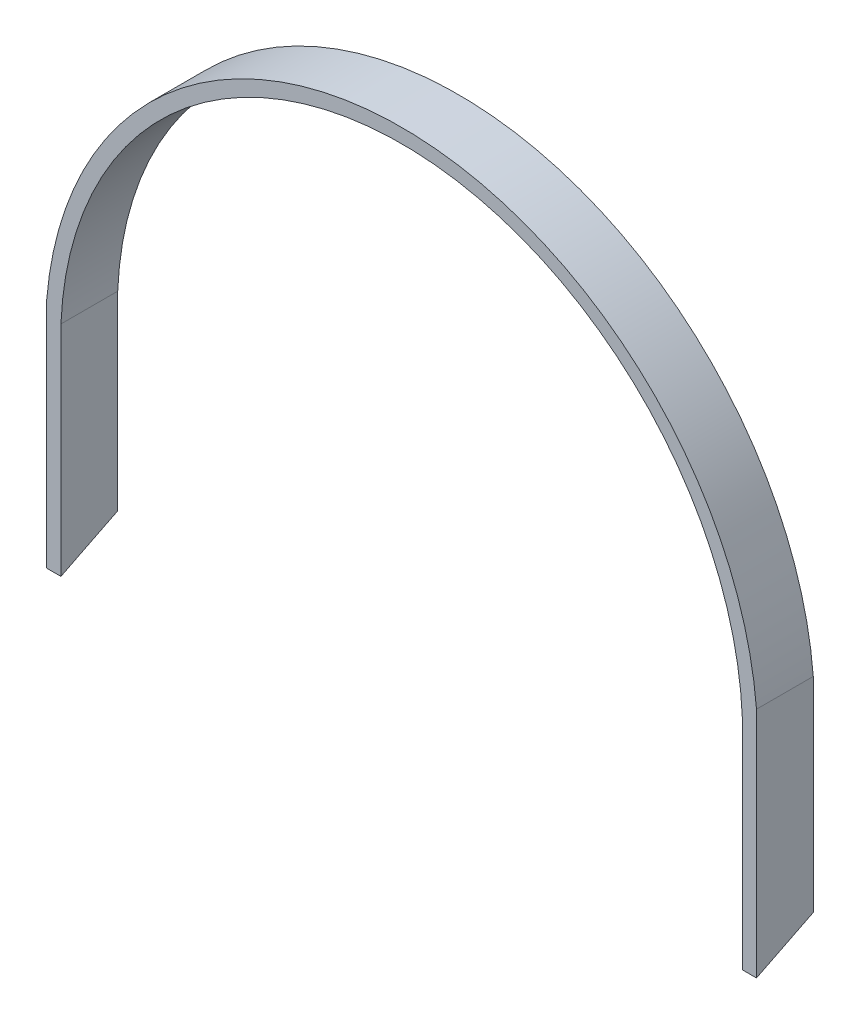
SolidWorks part; units mm, degrees
material "ABS"
ref_plane "Plan de face" through (0, 0, 0) normal (0, 0, 1) x (1, 0, 0)
ref_plane "Plan de dessus" through (0, 0, 0) normal (0, 1, 0) x (1, 0, 0)
ref_plane "Plan de droite" through (0, 0, 0) normal (1, 0, 0) x (0, 0, -1)
sketch "Esquisse1" plane through (0, 0, 0) normal (0, 0, 1) x (1, 0, 0)
  line L2 (0, 0) -> (0, 197) construction
  line L3 (0, 197) -> (250, 197) construction
  line L4 (250, 0) -> (250, 197) construction
  line L6 (5, 0) -> (5, 77)
  line L8 (245, 0) -> (245, 77)
  line L14 (0, 0) -> (5, 0)
  line L15 (250, 0) -> (245, 0)
  line L16 (5, 77) -> (5, 197) construction
  line L17 (0, 0) -> (0, 82)
  line L18 (250, 0) -> (250, 82)
  line L19 (125, 192) -> (125, 197) construction
  arc A2 (0, 82) -> (250, 82) centre (125, 71.5652) cw
  arc A3 (245, 77) -> (5, 77) centre (125, 71.8913) ccw
  point P14 (125, 197)
extrude "Boss.-Extru.1" add sketch "Esquisse1" along normal blind 20
sketch "Esquisse2" plane through (250, 0, 0) normal (1, 0, 0) x (0, 0, -1)
  line L0 (-20, 0) -> (0, 0)
  line L1 (0, 0) -> (0, 10)
  line L2 (0, 0) -> (0, 82) construction
  line L3 (0, 10) -> (-20, 0)
  dimension "D1" = 10
extrude "Enlèv. mat.-Extru.1" cut sketch "Esquisse2" against normal through all
